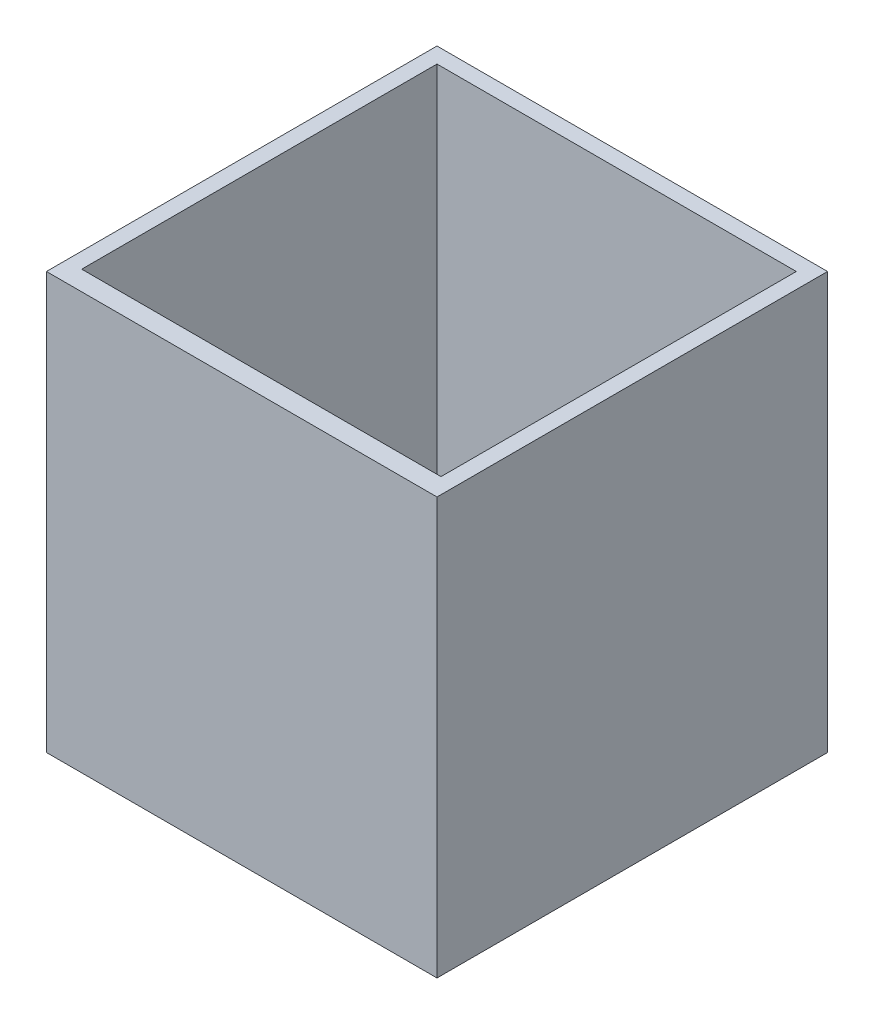
SolidWorks part; units mm, degrees
ref_plane "Front Plane" through (0, 0, 0) normal (0, 0, 1) x (1, 0, 0)
ref_plane "Top Plane" through (0, 0, 0) normal (0, 1, 0) x (1, 0, 0)
ref_plane "Right Plane" through (0, 0, 0) normal (1, 0, 0) x (0, 0, -1)
sketch "Sketch1" plane through (0, 0, 0) normal (0, 0, 1) x (1, 0, 0)
  line L1 (-37.5, -40) -> (37.5, -40)
  line L2 (-37.5, -40) -> (-37.5, 40)
  line L3 (-37.5, 40) -> (37.5, 40)
  line L4 (37.5, -40) -> (37.5, 40)
  line L5 (-37.5, -40) -> (37.5, 40) construction
  line L6 (-37.5, 40) -> (37.5, -40) construction
  point P0 (0, 0)
  dimension "D1" = 80
  dimension "D2" = 75
extrude "Boss-Extrude1" add sketch "Sketch1" along normal blind 75
sketch "Sketch2" plane through (0, 40, 0) normal (0, 1, 0) x (1, 0, 0)
  line L0 (-37.5, -75) -> (-37.5, 0) construction
  line L1 (-34.5, -71.2305) -> (34.5, -71.2305)
  line L2 (-34.5, -71.2305) -> (-34.5, -3)
  line L3 (-34.5, -3) -> (34.5, -3)
  line L4 (34.5, -71.2305) -> (34.5, -3)
  line L5 (37.5, 0) -> (-37.5, 0) construction
  line L6 (37.5, -75) -> (37.5, 0) construction
  dimension "D1" = 3
  dimension "D2" = 3
  dimension "D3" = 3
extrude "Cut-Extrude1" cut sketch "Sketch2" against normal blind 75
sketch "Sketch3" plane through (0, -35, 0) normal (0, 1, 0) x (1, 0, 0)
  line L5 (-34.5, -71.2305) -> (34.5, -71.2305) construction
  line L6 (-2.6823, -71.2305) -> (4.3177, -71.2305)
  line L7 (-2.6823, -71.2305) -> (-2.6823, -66.2305)
  line L8 (-2.6823, -66.2305) -> (4.3177, -66.2305)
  line L9 (4.3177, -71.2305) -> (4.3177, -66.2305)
  dimension "D1" = 7
  dimension "D2" = 5
extrude "Cut-Extrude2" cut sketch "Sketch3" against normal blind 75
sketch "Sketch4" plane through (-37.5, 0, 0) normal (-1, 0, 0) x (0, 0, 1)
  text T0 "  R.P.\r\nSINGH" font "Century Gothic" height in points 48
extrude "Boss-Extrude2" add sketch "Sketch4" along normal blind 1.5
